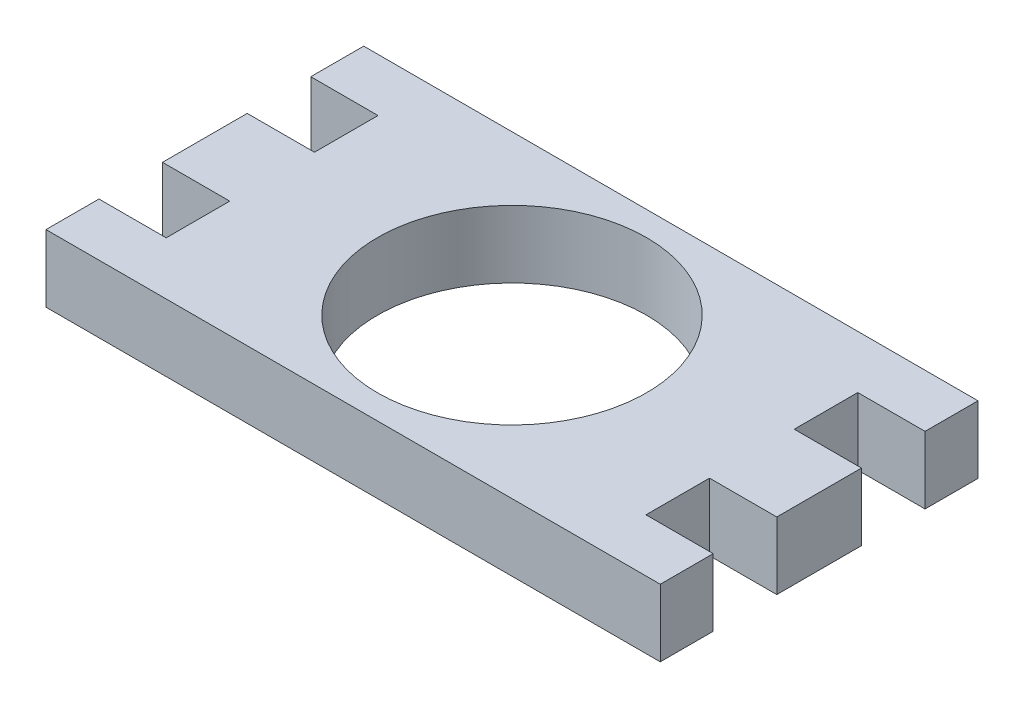
SolidWorks part; units mm, degrees
ref_plane "Front Plane" through (0, 0, 0) normal (0, 0, 1) x (1, 0, 0)
ref_plane "Top Plane" through (0, 0, 0) normal (0, 1, 0) x (1, 0, 0)
ref_plane "Right Plane" through (0, 0, 0) normal (1, 0, 0) x (0, 0, -1)
sketch "Sketch1" plane through (0, 0, 0) normal (0, 1, 0) x (1, 0, 0)
  line L0 (-29, 0) -> (0, 0) construction
  line L1 (-29, 15) -> (29, 15)
  line L2 (-29, 15) -> (-29, 10)
  line L3 (-29, -15) -> (29, -15)
  line L5 (0, 15) -> (0, -15) construction
  line L6 (29, -10) -> (29, -15)
  line L7 (29, -10) -> (22.65, -10)
  line L8 (-29, -10) -> (-22.65, -10)
  line L9 (-22.65, -10) -> (-22.65, -4)
  line L10 (-22.65, -4) -> (-29, -4)
  line L11 (-29, 4) -> (-29, -4)
  line L12 (-29, -10) -> (-29, -15)
  line L13 (-29, 10) -> (-22.65, 10)
  line L14 (-22.65, 10) -> (-22.65, 4)
  line L15 (-22.65, 4) -> (-29, 4)
  line L16 (22.65, -10) -> (22.65, -4)
  line L17 (22.65, -4) -> (29, -4)
  line L18 (29, 4) -> (29, -4)
  line L19 (22.65, 4) -> (29, 4)
  line L20 (22.65, 10) -> (22.65, 4)
  line L21 (29, 10) -> (22.65, 10)
  line L22 (29, 15) -> (29, 10)
  circle A0 centre (0, 0) radius 12.7
  dimension "D1" = 25.4
  dimension "D2" = 6.35
  dimension "D3" = 8
  dimension "D4" = 6
  dimension "D5" = 29
  dimension "D6" = 30
extrude "Boss-Extrude1" add sketch "Sketch1" along normal blind 6.35
